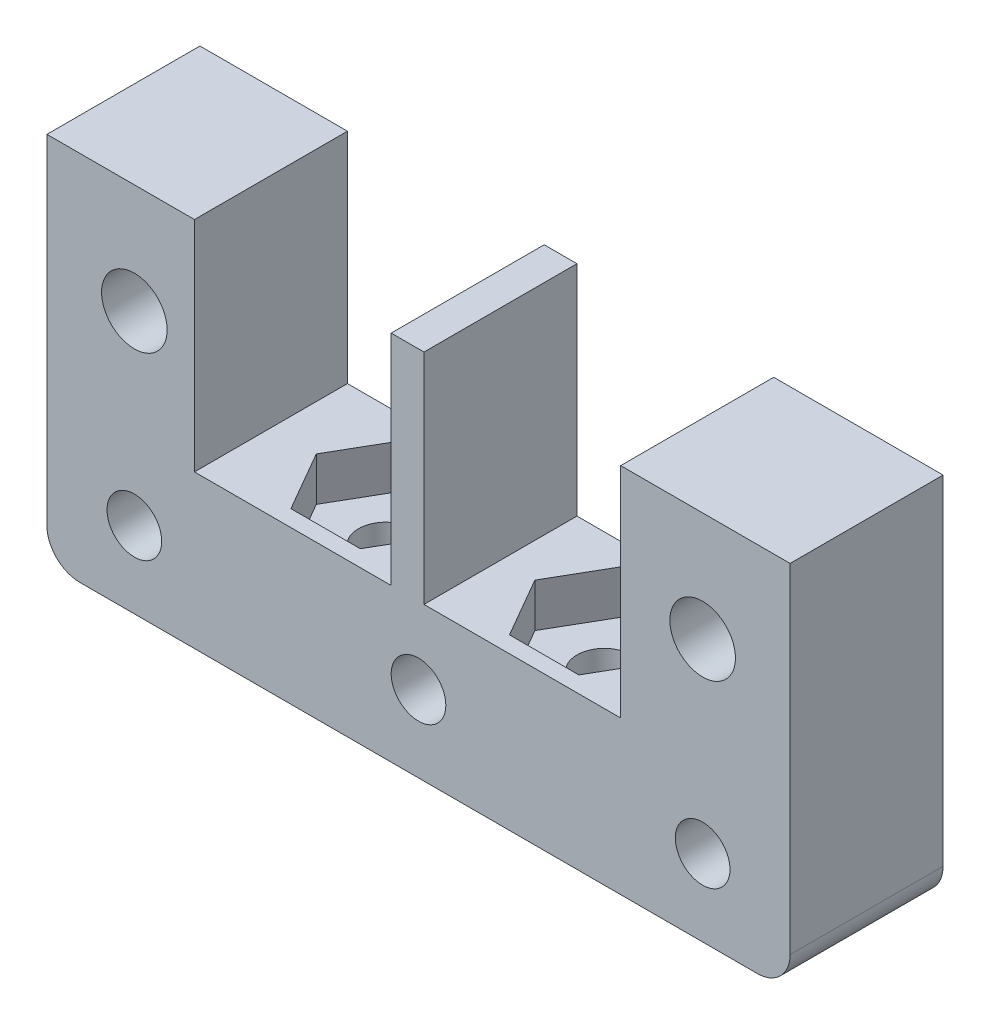
SolidWorks part; units mm, degrees
ref_plane "Front Plane" through (0, 0, 0) normal (0, 0, 1) x (1, 0, 0)
ref_plane "Top Plane" through (0, 0, 0) normal (0, 1, 0) x (1, 0, 0)
ref_plane "Right Plane" through (0, 0, 0) normal (1, 0, 0) x (0, 0, -1)
sketch "Sketch1" plane through (0, 0, 0) normal (0, 0, 1) x (1, 0, 0)
  line L0 (4, 3.5) -> (30, 3.5) construction
  line L1 (0, 0) -> (34, 0)
  line L3 (0, 7) -> (34, 7)
  line L4 (34, 0) -> (34, 7)
  line L5 (0, 7) -> (0, 0)
  circle A2 centre (4, 3.5) radius 1.25
  circle A3 centre (30, 3.5) radius 1.25
  circle A4 centre (17, 3.5) radius 1.25
  dimension "D4" = 17
  dimension "D1" = 26
  dimension "D3" = 3.5
  dimension "D2" = 34
extrude "Boss-Extrude1" add sketch "Sketch1" along normal blind 7
sketch "Sketch3" plane through (0, 0, 0) normal (0, -1, 0) x (1, 0, 0)
  line L0 (0, 7) -> (34, 7) construction
  line L1 (0, 7) -> (0, 0) construction
  line L2 (34, 7) -> (34, 0) construction
  circle A0 centre (22, 3.5) radius 1.25
  circle A1 centre (12, 3.5) radius 1.25
  dimension "D1" = 2.5
  dimension "D2" = 3.5
  dimension "D3" = 22
  dimension "D4" = 22
extrude "Cut-Extrude1" cut sketch "Sketch3" against normal blind 10
sketch "Sketch4" plane through (0, 7, 0) normal (0, 1, 0) x (1, 0, 0)
  line L0 (34, 0) -> (0, 0) construction
  line L1 (6.75, 0) -> (0, 0)
  line L2 (6.75, 0) -> (6.75, -7)
  line L3 (6.75, -7) -> (0, -7)
  line L4 (0, 0) -> (0, -7)
  line L6 (34, -7) -> (0, -7) construction
  line L8 (15.75, -7) -> (17.25, -7)
  line L9 (15.75, -7) -> (15.75, 0)
  line L10 (15.75, 0) -> (17.25, 0)
  line L11 (17.25, -7) -> (17.25, 0)
  line L12 (26.25, 0) -> (34, 0)
  line L13 (26.25, 0) -> (26.25, -7)
  line L14 (26.25, -7) -> (34, -7)
  line L15 (34, 0) -> (34, -7)
  circle A4 centre (12, -3.5) radius 1.25 construction
  point P14 (0, 0)
  point P15 (29.25, 0)
  point P21 (34, 0)
  dimension "D6" = 3.75
  dimension "D3" = 9
  dimension "D4" = 1.5
  dimension "D5" = 9
extrude "Boss-Extrude2" add sketch "Sketch4" along normal blind 10
fillet "Fillet1" [suppressed] radius 3.5
sketch "Sketch5" plane through (0, 7, 0) normal (0, 1, 0) x (1, 0, 0)
  line L1 (15.1754, -3.5) -> (13.5877, -0.75)
  line L2 (13.5877, -0.75) -> (10.4123, -0.75)
  line L3 (10.4123, -0.75) -> (8.8246, -3.5)
  line L4 (8.8246, -3.5) -> (10.4123, -6.25)
  line L5 (10.4123, -6.25) -> (13.5877, -6.25)
  line L6 (13.5877, -6.25) -> (15.1754, -3.5)
  line L7 (25.1754, -3.5) -> (23.5877, -0.75)
  line L8 (23.5877, -0.75) -> (20.4123, -0.75)
  line L9 (20.4123, -0.75) -> (18.8246, -3.5)
  line L10 (18.8246, -3.5) -> (20.4123, -6.25)
  line L11 (20.4123, -6.25) -> (23.5877, -6.25)
  line L12 (23.5877, -6.25) -> (25.1754, -3.5)
  circle A0 centre (12, -3.5) radius 2.75 construction
  circle A1 centre (22, -3.5) radius 2.75 construction
  dimension "D1" = 5.5
  dimension "D2" = 5.5
extrude "Cut-Extrude2" cut sketch "Sketch5" against normal blind 2
sketch "Sketch6" plane through (0, 0, 7) normal (0, 0, 1) x (1, 0, 0)
  line L1 (7.1754, 3.5) -> (5.5877, 6.25)
  line L2 (5.5877, 6.25) -> (2.4123, 6.25)
  line L3 (2.4123, 6.25) -> (0.8246, 3.5)
  line L4 (0.8246, 3.5) -> (2.4123, 0.75)
  line L5 (2.4123, 0.75) -> (5.5877, 0.75)
  line L6 (5.5877, 0.75) -> (7.1754, 3.5)
  line L7 (20.1754, 3.5) -> (18.5877, 6.25)
  line L8 (18.5877, 6.25) -> (15.4123, 6.25)
  line L9 (15.4123, 6.25) -> (13.8246, 3.5)
  line L10 (13.8246, 3.5) -> (15.4123, 0.75)
  line L11 (15.4123, 0.75) -> (18.5877, 0.75)
  line L12 (18.5877, 0.75) -> (20.1754, 3.5)
  line L13 (33.1754, 3.5) -> (31.5877, 6.25)
  line L14 (31.5877, 6.25) -> (28.4123, 6.25)
  line L15 (28.4123, 6.25) -> (26.8246, 3.5)
  line L16 (26.8246, 3.5) -> (28.4123, 0.75)
  line L17 (28.4123, 0.75) -> (31.5877, 0.75)
  line L18 (31.5877, 0.75) -> (33.1754, 3.5)
  circle A0 centre (4, 3.5) radius 2.75 construction
  circle A1 centre (17, 3.5) radius 2.75 construction
  circle A2 centre (30, 3.5) radius 2.75 construction
  dimension "D1" = 5.5
  dimension "D2" = 5.5
  dimension "D3" = 5.5
extrude "Cut-Extrude3" [suppressed] cut sketch "Sketch6" against normal blind 3
fillet "Fillet4" radius 1.5 2 edges at (0, 0, 3.5) (34, 0, 3.5)
sketch "Sketch7" plane through (0, 0, 0) normal (0, 0, -1) x (-1, 0, 0)
  line L0 (-34, 17) -> (-26.25, 17) construction
  line L1 (-4, 12) -> (-4, 3.5) construction
  line L2 (-30, 12) -> (-30, 3.5) construction
  circle A0 centre (-30, 12) radius 1.5
  circle A1 centre (-4, 12) radius 1.5
  point P4 (0, 0)
  point P10 (-30.0051, 3.9572)
  point P11 (-30, 3.5)
  dimension "D1" = 3
  dimension "D2" = 5
extrude "Cut-Extrude4" cut sketch "Sketch7" against normal blind 10
